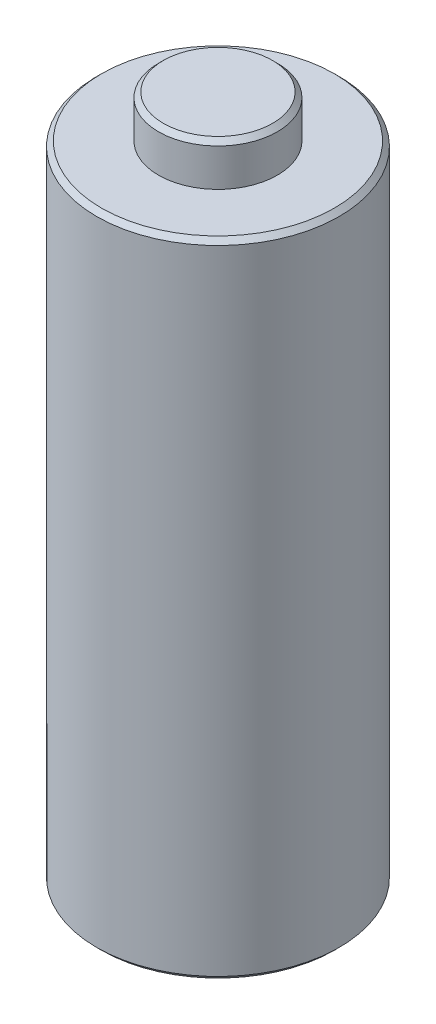
SolidWorks part; units mm, degrees
ref_plane "Front Plane" through (0, 0, 0) normal (0, 0, 1) x (1, 0, 0)
ref_plane "Top Plane" through (0, 0, 0) normal (0, 1, 0) x (1, 0, 0)
ref_plane "Right Plane" through (0, 0, 0) normal (1, 0, 0) x (0, 0, -1)
sketch "Sketch1" plane through (0, 0, 0) normal (0, 1, 0) x (1, 0, 0)
  circle A0 centre (0, 0) radius 2.45
  dimension "D1" = 4.9
extrude "Boss-Extrude1" add sketch "Sketch1" along normal blind 30
chamfer "Chamfer1" distance 0.2 angle 45 2 edges at (0, 30, 2.45) (0, 0, 2.45)
ref_plane "Plane1" through (0, 15, 0) normal (0, 1, 0) x (1, 0, 0)
sketch "Sketch2" plane through (0, 15, 0) normal (0, 1, 0) x (1, 0, 0)
  circle A0 centre (0, 0) radius 5
  dimension "D1" = 10
extrude "Boss-Extrude2" add sketch "Sketch2" along normal mid plane 26.5
chamfer "Chamfer2" distance 0.2 angle 45 2 edges at (0, 1.75, 5) (0, 28.25, 5)
